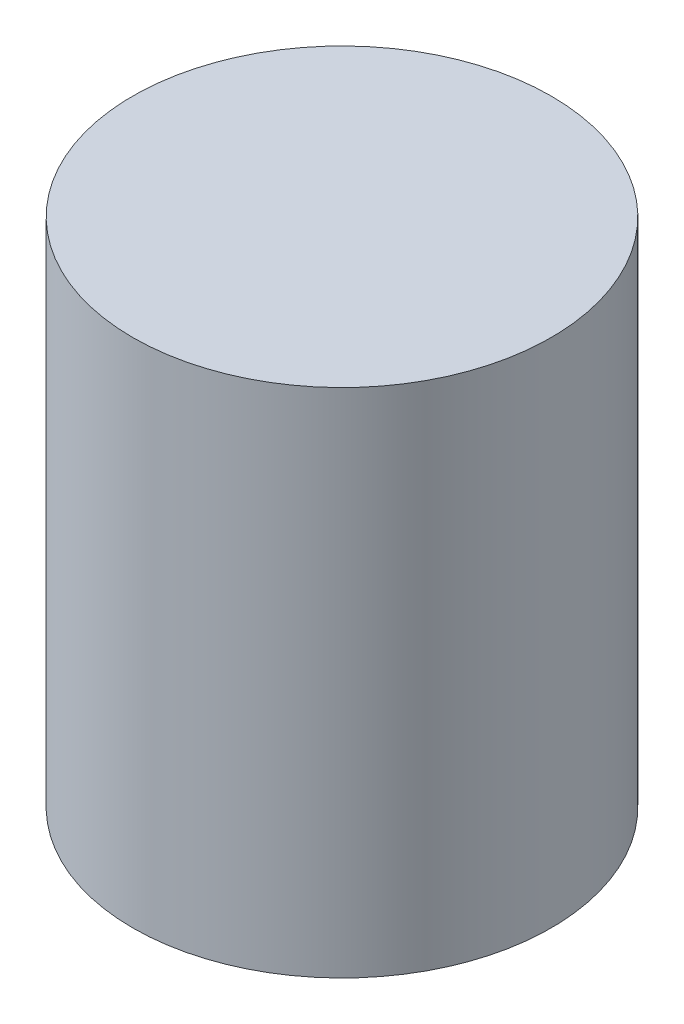
SolidWorks part; units mm, degrees
ref_plane "Front Plane" through (0, 0, 0) normal (0, 0, 1) x (1, 0, 0)
ref_plane "Top Plane" through (0, 0, 0) normal (0, 1, 0) x (1, 0, 0)
ref_plane "Right Plane" through (0, 0, 0) normal (1, 0, 0) x (0, 0, -1)
sketch "Sketch1" plane through (0, 0, 0) normal (0, 1, 0) x (1, 0, 0)
  circle A0 centre (0, 0) radius 13.5
  dimension "D1" = 27
extrude "Boss-Extrude1" add sketch "Sketch1" along normal blind 33
